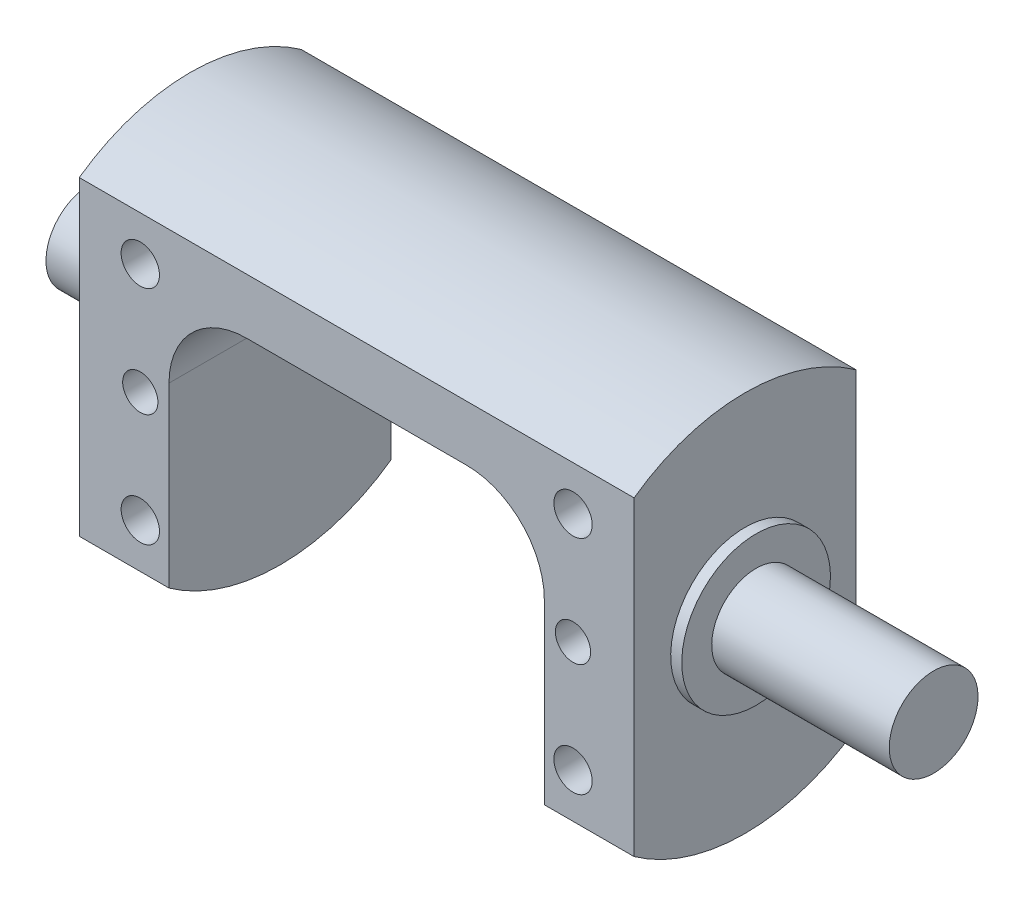
SolidWorks part; units mm, degrees
material "AISI 316 Annealed Stainless Steel Bar (SS)"
ref_plane "Front Plane" through (0, 0, 0) normal (0, 0, 1) x (1, 0, 0)
ref_plane "Top Plane" through (0, 0, 0) normal (0, 1, 0) x (1, 0, 0)
ref_plane "Right Plane" through (0, 0, 0) normal (1, 0, 0) x (0, 0, -1)
sketch "Sketch1" plane through (0, 0, 0) normal (1, 0, 0) x (0, 0, -1)
  line L0 (0, 17.2047) -> (0, 0)
  line L1 (-10, -14) -> (10, -14)
  line L2 (-10, -14) -> (-10, 14)
  line L3 (-10, 14) -> (10, 14)
  line L4 (10, -14) -> (10, 14)
  line L5 (-10, -14) -> (10, 14) construction
  line L6 (-10, 14) -> (10, -14) construction
  circle A0 centre (0, 0) radius 17.2047
  dimension "D1" = 20
  dimension "D2" = 28
sketch "Sketch2" plane through (0, 0, 0) normal (0, 0, 1) x (1, 0, 0)
  line L0 (-34, 0) -> (42, 0)
  line L1 (42, 0) -> (42, 4)
  line L2 (42, 4) -> (26, 4)
  line L3 (25, 6.7) -> (25, 17.2047)
  line L4 (25, 17.2047) -> (-25, 17.2047)
  line L5 (-25, 17.2047) -> (-25, 6.7)
  line L6 (-27.5, 4) -> (-34, 4)
  line L7 (-34, 4) -> (-34, 0)
  line L10 (26, 4) -> (26, 6.7)
  line L11 (26, 6.7) -> (25, 6.7)
  line L12 (-25, 6.7) -> (-27.5, 6.7)
  line L13 (-27.5, 6.7) -> (-27.5, 4)
  dimension "D1" = 4
  dimension "D2" = 2.5
  dimension "D3" = 42
  dimension "D4" = 50
  dimension "D5" = 6.7
  dimension "D6" = 9
  dimension "D7" = 1
revolve "Revolve1" add sketch "Sketch2" angle 360 about L0
sketch "Sketch3" plane through (-25, 0, 0) normal (-1, 0, 0) x (0, 0, 1)
  line L2 (10, -14) -> (10, 14) construction
  line L3 (-10, 17.2047) -> (10, 17.2047)
  line L4 (-10, 17.2047) -> (-10, -17.2047)
  line L5 (-10, -17.2047) -> (10, -17.2047)
  line L6 (10, 17.2047) -> (10, -17.2047)
  line L7 (-10, -14) -> (-10, 14) construction
  circle A0 centre (0, 0) radius 17.2047 construction
extrude "Cut-Extrude1" cut sketch "Sketch3" against normal through all both and the other way through all flip side to cut
hole_wizard "#8-32 Tapped Hole1" positions "Sketch4" profile "Sketch5" tap size "#8-32" standard "ANSI Inch"
sketch "Sketch4" plane through (0, 0, -10) normal (0, 0, -1) x (-1, 0, 0)
  line L1 (-19.5, 10) -> (19.5, 10)
  line L2 (-19.5, 10) -> (-19.5, -10)
  line L3 (-19.5, -10) -> (19.5, -10)
  line L4 (19.5, 10) -> (19.5, -10)
  line L6 (-25, 14) -> (-25, -14) construction
  line L7 (-19.5, 0) -> (0, 0) construction
  line L8 (0, 0) -> (0, 10) construction
  point P1 (-19.5, 10)
  point P2 (19.5, -10)
  point P53 (-19.5, -10)
  point P54 (19.5, 10)
  dimension "D1" = 5.5
  dimension "D2" = 20
sketch "Sketch5" plane through (19.5, 10, -10) normal (1, 0, 0) x (0, 1, 0)
  line L0 (0, 0) -> (0, 11.7478)
  line L1 (0, 11.7478) -> (1.7272, 10.71)
  line L2 (1.7272, 10.71) -> (1.7272, 0)
  line L5 (1.7272, 0) -> (0, 0)
  line L10 (0, 11.7478) -> (-1.7272, 10.71) construction
  line L11 (0, -6.35) -> (0, 107.95) construction
  dimension "Tap Drill Dia." = 3.4544
  dimension "Tap Drill Depth" = 10.71
  dimension "Drill Angle" = 118
cosmetic thread "Hole Thread1" parameters "D1"=8.33, "D2"=4.1656
cosmetic thread "Hole Thread2" parameters "D1"=8.33, "D2"=4.1656
cosmetic thread "Hole Thread3" parameters "D1"=8.33, "D2"=4.1656
cosmetic thread "Hole Thread4" parameters "D1"=8.33, "D2"=4.1656
hole_wizard "1/8 (0.1250) Dowel Hole1" positions "Sketch6" profile "Sketch7" hole size "1/8" standard "ANSI Inch"
sketch "Sketch6" plane through (0, 0, -10) normal (0, 0, -1) x (-1, 0, 0)
  line L0 (-19.5, 10) -> (-19.5, -10) construction
  line L1 (19.5, 10) -> (19.5, -10) construction
  point P0 (-19.5, 0)
  point P2 (19.5, 0)
sketch "Sketch7" plane through (19.5, 0, -10) normal (1, 0, 0) x (0, 1, 0)
  line L0 (0, 0) -> (0, 6.9539)
  line L1 (0, 6.9539) -> (1.5875, 6)
  line L2 (1.5875, 6) -> (1.5875, 0)
  line L5 (1.5875, 0) -> (0, 0)
  line L10 (0, 6.9539) -> (-1.5875, 6) construction
  line L11 (0, -6.35) -> (0, 107.95) construction
  dimension "Hole Dia." = 3.175
  dimension "Hole Depth" = 6
  dimension "Drill Angle" = 118
mirror "Mirror1" about plane through (0, 0, 0) normal (0, 0, 1) of "1/8 (0.1250) Dowel Hole1", "#8-32 Tapped Hole1"
cosmetic thread "Hole Thread5" parameters "D1"=8.33, "D2"=4.1656
cosmetic thread "Hole Thread6" parameters "D1"=8.33, "D2"=4.1656
cosmetic thread "Hole Thread7" parameters "D1"=8.33, "D2"=4.1656
cosmetic thread "Hole Thread8" parameters "D1"=8.33, "D2"=4.1656
hole_wizard "#8-32 Tapped Hole2" positions "Sketch8" profile "Sketch10" tap size "#8-32" standard "ANSI Inch"
sketch "Sketch8" plane through (-34, 0, 0) normal (-1, 0, 0) x (0, 0, 1)
  point P0 (0, 0)
sketch "Sketch10" plane through (-34, 0, 0) normal (0, 1, 0) x (0, 0, 1)
  line L0 (0, 0) -> (0, 11.7478)
  line L1 (0, 11.7478) -> (1.7272, 10.71)
  line L2 (1.7272, 10.71) -> (1.7272, 0)
  line L5 (1.7272, 0) -> (0, 0)
  line L10 (0, 11.7478) -> (-1.7272, 10.71) construction
  line L11 (0, -6.35) -> (0, 107.95) construction
  dimension "Tap Drill Dia." = 3.4544
  dimension "Tap Drill Depth" = 10.71
  dimension "Drill Angle" = 118
cosmetic thread "Hole Thread9" parameters "D1"=8.33, "D2"=4.1656
sketch "Sketch11" plane through (0, 0, 10) normal (0, 0, 1) x (1, 0, 0)
  line L0 (25, 14) -> (-25, 14) construction
  line L1 (-4.7728, 14) -> (4.7728, 14)
  line L2 (-14.7728, 4) -> (-14.7728, -4)
  line L3 (-4.7728, -14) -> (4.7728, -14)
  line L4 (14.7728, 4) -> (14.7728, -4)
  line L5 (-25, -14) -> (25, -14) construction
  line L6 (0, 0) -> (0, 14) construction
  circle A0 centre (-19.5, 10) radius 1.7272 construction
  arc A1 (4.7728, -14) -> (14.7728, -4) centre (4.7728, -4) ccw
  arc A2 (-14.7728, -4) -> (-4.7728, -14) centre (-4.7728, -4) ccw
  arc A3 (4.7728, 14) -> (14.7728, 4) centre (4.7728, 4) cw
  arc A4 (-4.7728, 14) -> (-14.7728, 4) centre (-4.7728, 4) ccw
  point P15 (14.7728, -14)
  point P22 (-14.7728, 14)
  dimension "D1" = 3
  dimension "D2" = 10
extrude "Cut-Extrude2" [suppressed] cut sketch "Sketch11" against normal through all
sketch "Sketch12" plane through (0, 0, 10) normal (0, 0, 1) x (1, 0, 0)
  line L0 (25, 14) -> (-25, 14) construction
  line L1 (-9.9125, -37.3916) -> (9.9125, -37.3916)
  line L2 (-16.9125, -30.3916) -> (-16.9125, 2)
  line L3 (-9.9125, 9) -> (9.9125, 9)
  line L4 (16.9125, -30.3916) -> (16.9125, 2)
  line L5 (-16.9125, -37.3916) -> (16.9125, 9) construction
  line L6 (-16.9125, 9) -> (16.9125, -37.3916) construction
  line L7 (0, 14) -> (0, -14.1958) construction
  circle A1 centre (19.5, 0) radius 1.5875 construction
  arc A2 (-9.9125, -37.3916) -> (-16.9125, -30.3916) centre (-9.9125, -30.3916) cw
  arc A3 (9.9125, -37.3916) -> (16.9125, -30.3916) centre (9.9125, -30.3916) ccw
  arc A4 (9.9125, 9) -> (16.9125, 2) centre (9.9125, 2) cw
  arc A5 (-16.9125, 2) -> (-9.9125, 9) centre (-9.9125, 2) cw
  point P0 (0, -14.1958)
  point P5 (0, 3.7038)
  point P22 (0, 0)
  point P26 (0, 3.7038)
  dimension "D3" = 7
  dimension "D1" = 5
  dimension "D2" = 1
extrude "Cut-Extrude3" cut sketch "Sketch12" against normal through all both and the other way through all
